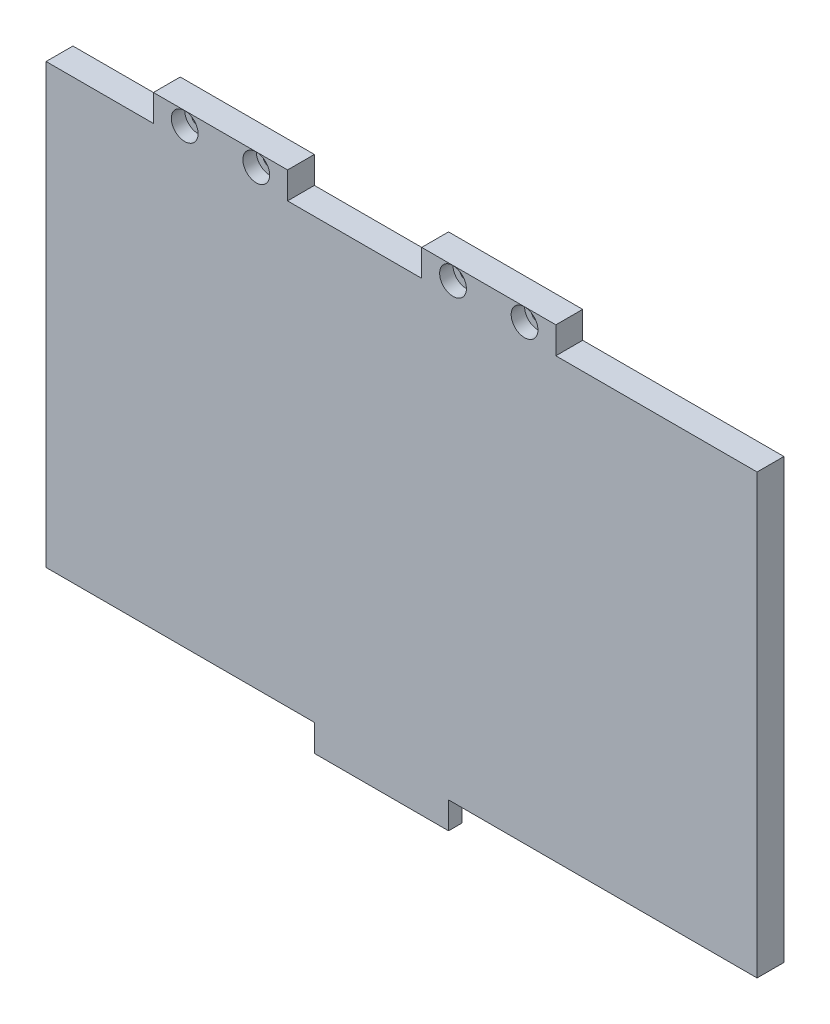
SolidWorks part; units mm, degrees
ref_plane "Plan de face" through (0, 0, 0) normal (0, 0, 1) x (1, 0, 0)
ref_plane "Plan de dessus" through (0, 0, 0) normal (0, 1, 0) x (1, 0, 0)
ref_plane "Plan de droite" through (0, 0, 0) normal (1, 0, 0) x (0, 0, -1)
sketch "Esquisse1" plane through (0, 0, 0) normal (0, 0, 1) x (1, 0, 0)
  line L1 (0, 0) -> (-159, 0)
  line L2 (0, 0) -> (0, 104)
  line L3 (0, 104) -> (-159, 104)
  line L4 (-159, 0) -> (-159, 104)
  dimension "D1" = 104
  dimension "D2" = 159
extrude "Boss.-Extru.1" add sketch "Esquisse1" along normal blind 6
sketch "Esquisse2" plane through (0, 0, 6) normal (0, 0, 1) x (1, 0, 0)
  line L0 (0, 104) -> (-159, 104) construction
  line L1 (-159, 104) -> (-135, 104)
  line L2 (-159, 104) -> (-159, 98)
  line L3 (-159, 98) -> (-135, 98)
  line L4 (-135, 104) -> (-135, 98)
  line L5 (0, 104) -> (-45, 104)
  line L6 (0, 104) -> (0, 98)
  line L7 (0, 98) -> (-45, 98)
  line L8 (-45, 104) -> (-45, 98)
  line L9 (-105, 104) -> (-75, 104)
  line L10 (-105, 104) -> (-105, 98)
  line L11 (-105, 98) -> (-75, 98)
  line L12 (-75, 104) -> (-75, 98)
  dimension "D1" = 6
  dimension "D2" = 6
  dimension "D3" = 6
  dimension "D4" = 45
  dimension "D5" = 30
  dimension "D6" = 30
  dimension "D7" = 30
extrude "Enlèv. mat.-Extru.1" cut sketch "Esquisse2" against normal through all
sketch "Esquisse3" plane through (0, 0, 6) normal (0, 0, 1) x (1, 0, 0)
  line L0 (-105, 104) -> (-135, 104) construction
  line L1 (-135, 98) -> (-135, 104) construction
  line L2 (-105, 104) -> (-105, 98) construction
  line L3 (-45, 104) -> (-75, 104) construction
  line L4 (-75, 98) -> (-75, 104) construction
  line L5 (-45, 104) -> (-45, 98) construction
  circle A0 centre (-128, 101) radius 1.5
  circle A1 centre (-112, 101) radius 1.5
  circle A2 centre (-68, 101) radius 1.5
  circle A3 centre (-52, 101) radius 1.5
  dimension "D1" = 3
  dimension "D2" = 3
  dimension "D3" = 3
  dimension "D4" = 7
  dimension "D5" = 3
  dimension "D6" = 7
  dimension "D7" = 3
  dimension "D8" = 3
  dimension "D9" = 7
  dimension "D10" = 3
  dimension "D11" = 3
  dimension "D12" = 7
extrude "Enlèv. mat.-Extru.2" cut sketch "Esquisse3" against normal through all
sketch "Esquisse4" plane through (0, 0, 6) normal (0, 0, 1) x (1, 0, 0)
  circle A0 centre (-128, 101) radius 2.995
  circle A1 centre (-112, 101) radius 2.995
  circle A2 centre (-68, 101) radius 2.995
  circle A3 centre (-52, 101) radius 2.995
  dimension "D1" = 5.99
  dimension "D2" = 5.99
  dimension "D3" = 5.99
  dimension "D4" = 5.99
extrude "Enlèv. mat.-Extru.3" cut sketch "Esquisse4" against normal blind 3
sketch "Esquisse5" plane through (0, 0, 0) normal (0, -1, 0) x (1, 0, 0)
  line L0 (-159, 6) -> (0, 6) construction
  line L1 (-99, 6) -> (-69, 6)
  line L2 (-99, 6) -> (-99, 0)
  line L3 (-99, 0) -> (-69, 0)
  line L4 (-69, 6) -> (-69, 0)
  line L5 (-159, 0) -> (0, 0) construction
  line L6 (-159, 6) -> (-159, 0) construction
  dimension "D1" = 30
  dimension "D2" = 60
extrude "Boss.-Extru.2" add sketch "Esquisse5" along normal blind 6
sketch "Esquisse6" plane through (0, 0, 0) normal (0, 0, -1) x (-1, 0, 0)
  line L1 (69, 0) -> (99, 0)
  line L2 (69, 0) -> (69, -6)
  line L3 (69, -6) -> (99, -6)
  line L4 (99, 0) -> (99, -6)
extrude "Enlèv. mat.-Extru.4" cut sketch "Esquisse6" against normal blind 3
